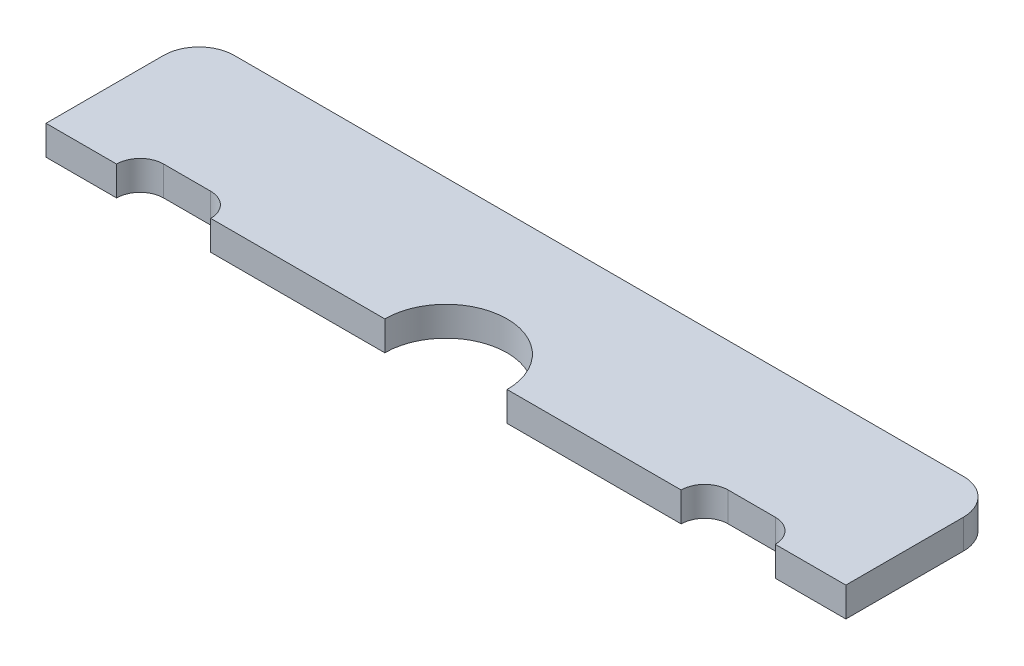
SolidWorks part; units mm, degrees
ref_plane "前视基准面" through (0, 0, 0) normal (0, 0, 1) x (1, 0, 0)
ref_plane "上视基准面" through (0, 0, 0) normal (0, 1, 0) x (1, 0, 0)
ref_plane "右视基准面" through (0, 0, 0) normal (1, 0, 0) x (0, 0, -1)
other "Configuration Table"
sketch "草图2" plane through (0, 0, 0) normal (0, 1, 0) x (1, 0, 0)
  line L0 (-17, 0) -> (-11, 0) construction
  line L1 (-15.5, 6.5) -> (15.5, 6.5)
  line L2 (-17, 5) -> (-17, -5) construction
  line L3 (-15.5, -6.5) -> (15.5, -6.5) construction
  line L4 (17, 5) -> (17, -5) construction
  line L5 (-17, 6.5) -> (17, -6.5) construction
  line L6 (-17, -6.5) -> (17, 6.5) construction
  line L7 (-17, 5) -> (-17, 0)
  line L8 (17, 5) -> (17, 0)
  line L9 (-12, 0) -> (-11, 0) construction
  line L10 (-17, 0) -> (-14, 0)
  line L15 (10.4, 0.8) -> (12, 0) construction
  line L16 (12, 0) -> (13.6, 0.8) construction
  line L21 (-10, 0) -> (17, 0) construction
  line L22 (-10, 0) -> (12, 0) construction
  line L23 (-10, 0) -> (-2.6, 0)
  line L24 (2.6, 0) -> (10, 0)
  line L25 (14, 0) -> (17, 0)
  line L26 (-13, 0) -> (-11, 0) construction
  line L27 (-13, 1) -> (-11, 1)
  line L29 (11, 0) -> (13, 0) construction
  line L30 (11, 1) -> (13, 1)
  arc A0 (-17, -5) -> (-15.5, -6.5) centre (-15.5, -5) ccw construction
  arc A1 (15.5, -6.5) -> (17, -5) centre (15.5, -5) ccw construction
  arc A2 (15.5, 6.5) -> (17, 5) centre (15.5, 5) cw
  arc A3 (-15.5, 6.5) -> (-17, 5) centre (-15.5, 5) ccw
  arc A4 (2.6, 0) -> (-2.6, 0) centre (0, 0) ccw
  arc A5 (-13, 1) -> (-14, 0) centre (-13, 0) ccw
  arc A6 (-10, 0) -> (-11, 1) centre (-11, 0) ccw
  arc A7 (11, 1) -> (10, 0) centre (11, 0) ccw
  arc A8 (14, 0) -> (13, 1) centre (13, 0) ccw
  point P0 (0, 0)
  point P22 (-12, 0)
  point P25 (0, 0)
  point P39 (12, 0)
  dimension "D1" = 1.5
extrude "凸台-拉伸1" add sketch "草图2" along normal blind 1.25
